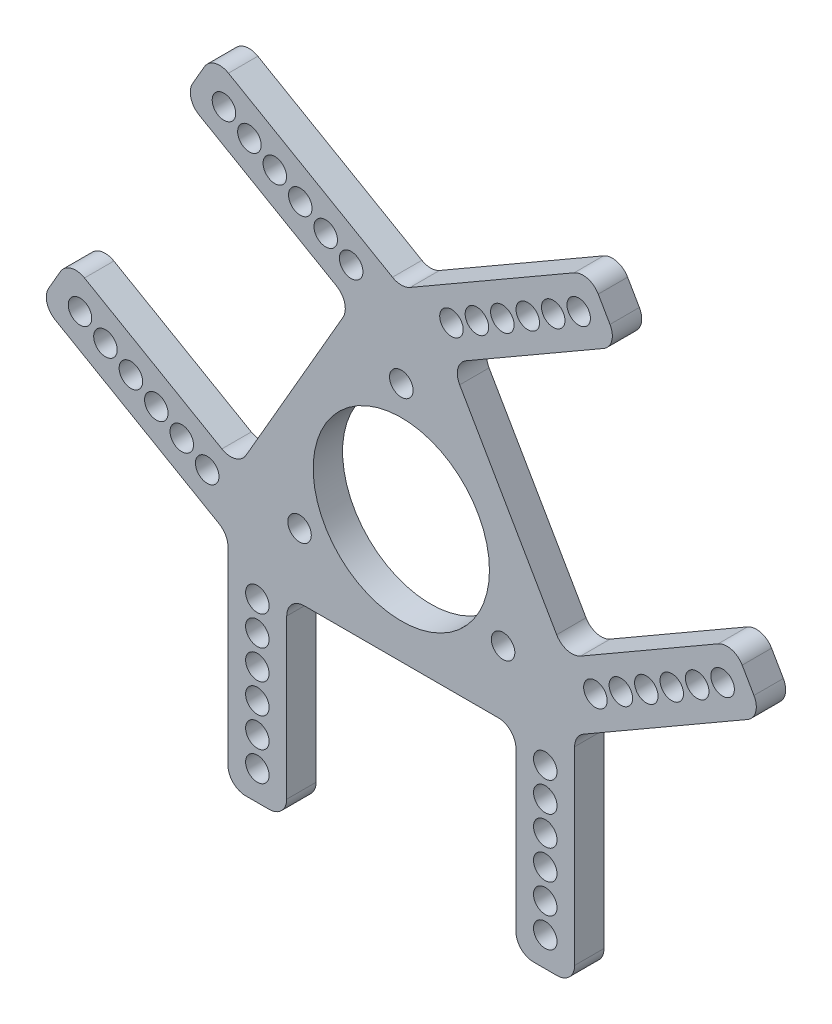
SolidWorks part; units mm, degrees
ref_plane "Front Plane" through (0, 0, 0) normal (0, 0, 1) x (1, 0, 0)
ref_plane "Top Plane" through (0, 0, 0) normal (0, 1, 0) x (1, 0, 0)
ref_plane "Right Plane" through (0, 0, 0) normal (1, 0, 0) x (0, 0, -1)
sketch "Sketch1" plane through (0, 0, 0) normal (0, 0, 1) x (1, 0, 0)
  line L0 (0, 0) -> (0, -24) construction
  line L1 (0, -24) -> (24.5, -24) construction
  line L2 (24.5, -24) -> (24.5, -17) construction
  line L3 (24.5, -17) -> (29.5, -17) construction
  line L4 (-24.5, -17) -> (-29.5, -17) construction
  line L5 (-24.5, -24) -> (-24.5, -17) construction
  line L6 (0, 0) -> (0, 20) construction
  line L7 (-33.0346, -9.2176) -> (-26.9724, -12.7176) construction
  line L8 (-26.9724, -12.7176) -> (-29.4724, -17.0477) construction
  line L9 (-2.4724, 29.7176) -> (0.0276, 34.0477) construction
  line L10 (-8.5346, 33.2176) -> (-2.4724, 29.7176) construction
  line L11 (8.5346, 33.2176) -> (2.4724, 29.7176) construction
  line L12 (2.4724, 29.7176) -> (-0.0276, 34.0477) construction
  line L13 (26.9724, -12.7176) -> (29.4724, -17.0477) construction
  line L14 (33.0346, -9.2176) -> (26.9724, -12.7176) construction
  line L15 (-19.5, -21) -> (19.5, -21)
  line L16 (19.5, -21) -> (19.5, -54)
  line L17 (19.5, -54) -> (29.5, -54)
  line L18 (29.5, -54) -> (29.5, 5.4848) construction
  line L19 (-19.5, -54) -> (-29.5, -54)
  line L20 (-29.5, -54) -> (-29.5, 5.4848) construction
  line L21 (-19.5, -21) -> (-19.5, -54)
  line L22 (-32.0154, 52.5477) -> (100.5692, -24) construction
  line L23 (-37.0154, 43.8875) -> (-32.0154, 52.5477)
  line L24 (-8.4365, 27.3875) -> (-37.0154, 43.8875)
  line L25 (-8.4365, 27.3875) -> (-27.9365, -6.3875)
  line L26 (-27.9365, -6.3875) -> (-56.5154, 10.1125)
  line L27 (-56.5154, 10.1125) -> (-61.5154, 1.4523)
  line L28 (-61.5154, 1.4523) -> (-10, -28.2902) construction
  line L29 (61.5154, 1.4523) -> (10, -28.2902) construction
  line L30 (56.5154, 10.1125) -> (61.5154, 1.4523)
  line L31 (27.9365, -6.3875) -> (56.5154, 10.1125)
  line L32 (27.9365, -6.3875) -> (8.4365, 27.3875)
  line L33 (8.4365, 27.3875) -> (37.0154, 43.8875)
  line L34 (37.0154, 43.8875) -> (32.0154, 52.5477)
  line L35 (32.0154, 52.5477) -> (-19.5, 22.8053) construction
  line L36 (-32.0154, 52.5477) -> (0, 34.0637)
  line L37 (0, 34.0637) -> (32.0154, 52.5477)
  line L38 (61.5154, 1.4523) -> (29.5, -17.0318)
  line L39 (29.5, -17.0318) -> (29.5, -54)
  line L40 (-29.5, -54) -> (-29.5, -17.0318)
  line L41 (-29.5, -17.0318) -> (-61.5154, 1.4523)
  circle A0 centre (24.5, -24) radius 2
  circle A1 centre (24.5, -29) radius 2
  circle A2 centre (24.5, -34) radius 2
  circle A3 centre (24.5, -39) radius 2
  circle A4 centre (24.5, -44) radius 2
  circle A5 centre (24.5, -49) radius 2
  circle A6 centre (-24.5, -49) radius 2
  circle A7 centre (-24.5, -44) radius 2
  circle A8 centre (-24.5, -39) radius 2
  circle A9 centre (-24.5, -34) radius 2
  circle A10 centre (-24.5, -29) radius 2
  circle A11 centre (-24.5, -24) radius 2
  circle A12 centre (-8.5346, 33.2176) radius 2
  circle A13 centre (-12.8647, 35.7176) radius 2
  circle A14 centre (-17.1949, 38.2176) radius 2
  circle A15 centre (-21.525, 40.7176) radius 2
  circle A16 centre (-25.8551, 43.2176) radius 2
  circle A17 centre (-30.1852, 45.7176) radius 2
  circle A18 centre (-33.0346, -9.2176) radius 2
  circle A19 centre (-37.3647, -6.7176) radius 2
  circle A20 centre (-41.6949, -4.2176) radius 2
  circle A21 centre (-46.025, -1.7176) radius 2
  circle A22 centre (-50.3551, 0.7824) radius 2
  circle A23 centre (-54.6852, 3.2824) radius 2
  circle A24 centre (33.0346, -9.2176) radius 2
  circle A25 centre (37.3647, -6.7176) radius 2
  circle A26 centre (41.6949, -4.2176) radius 2
  circle A27 centre (46.025, -1.7176) radius 2
  circle A28 centre (50.3551, 0.7824) radius 2
  circle A29 centre (54.6852, 3.2824) radius 2
  circle A30 centre (8.5346, 33.2176) radius 2
  circle A31 centre (12.8647, 35.7176) radius 2
  circle A32 centre (17.1949, 38.2176) radius 2
  circle A33 centre (21.525, 40.7176) radius 2
  circle A34 centre (25.8551, 43.2176) radius 2
  circle A35 centre (30.1852, 45.7176) radius 2
  circle A36 centre (0, 20) radius 2
  circle A37 centre (17.3205, -10) radius 2
  circle A38 centre (-17.3205, -10) radius 2
  circle A39 centre (0, 0) radius 15
  point P81 (0, 0)
  point P88 (0, 0)
  point P102 (0, 0)
  point P110 (0, -21)
  point P129 (0, 0)
  dimension "D4" = 4
  dimension "D8" = 4
  dimension "D10" = 30
  dimension "D1" = 24.5
  dimension "D2" = 29.5
  dimension "D3" = 7
  dimension "D7" = 20
  dimension "D12" = 24
  dimension "D13" = 5
  dimension "D14" = 5
  dimension "D15" = 5
  dimension "D16" = 6
  dimension "D5" = 6
  dimension "D6" = 3
  dimension "D9" = 3
  dimension "D11" = 3
  dimension "D17" = 3
extrude "Boss-Extrude1" add sketch "Sketch1" along normal blind 5
fillet "Fillet1" radius 3 21 edges at (0, 34.0637, 2.5) (32.0154, 52.5477, 2.5) (37.0154, 43.8875, 2.5) (8.4365, 27.3875, 2.5) (27.9365, -6.3875, 2.5) (56.5154, 10.1125, 2.5) (61.5154, 1.4523, 2.5) (29.5, -17.0318, 2.5) (29.5, -54, 2.5) (19.5, -54, 2.5) (19.5, -21, 2.5) (-19.5, -21, 2.5) (-27.9365, -6.3875, 2.5) (-8.4365, 27.3875, 2.5) (-32.0154, 52.5477, 2.5) (-37.0154, 43.8875, 2.5) (-56.5154, 10.1125, 2.5) (-61.5154, 1.4523, 2.5) (-29.5, -17.0318, 2.5) (-19.5, -54, 2.5) (-29.5, -54, 2.5)
